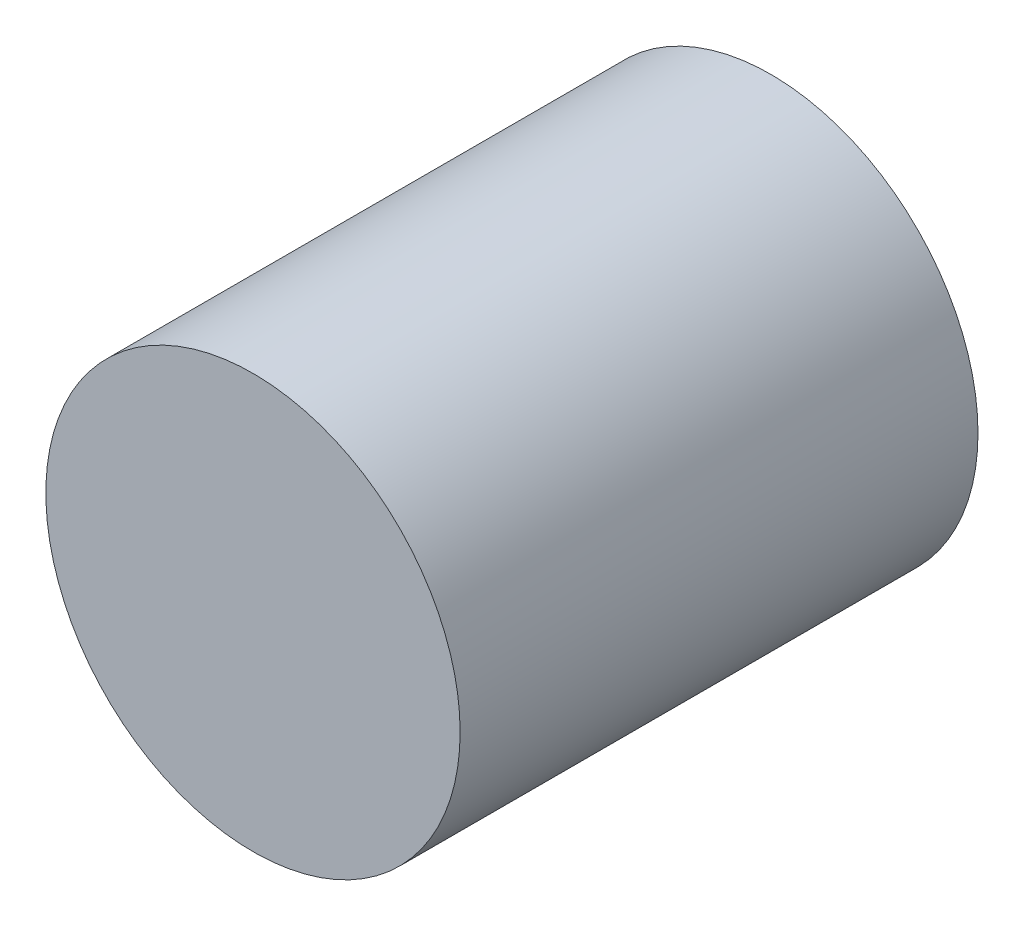
SolidWorks part; units mm, degrees
material "ｱｸﾘﾙ (中-上級の耐衝撃性)"
ref_plane "正面" through (0, 0, 0) normal (0, 0, 1) x (1, 0, 0)
ref_plane "平面" through (0, 0, 0) normal (0, 1, 0) x (1, 0, 0)
ref_plane "右側面" through (0, 0, 0) normal (1, 0, 0) x (0, 0, -1)
sketch "ｽｹｯﾁ1" plane through (0, 0, 0) normal (0, 0, 1) x (1, 0, 0)
  circle A0 centre (0, 0) radius 200
  dimension "D1" = 400
extrude "ﾎﾞｽ - 押し出し1" add sketch "ｽｹｯﾁ1" along normal blind 500
